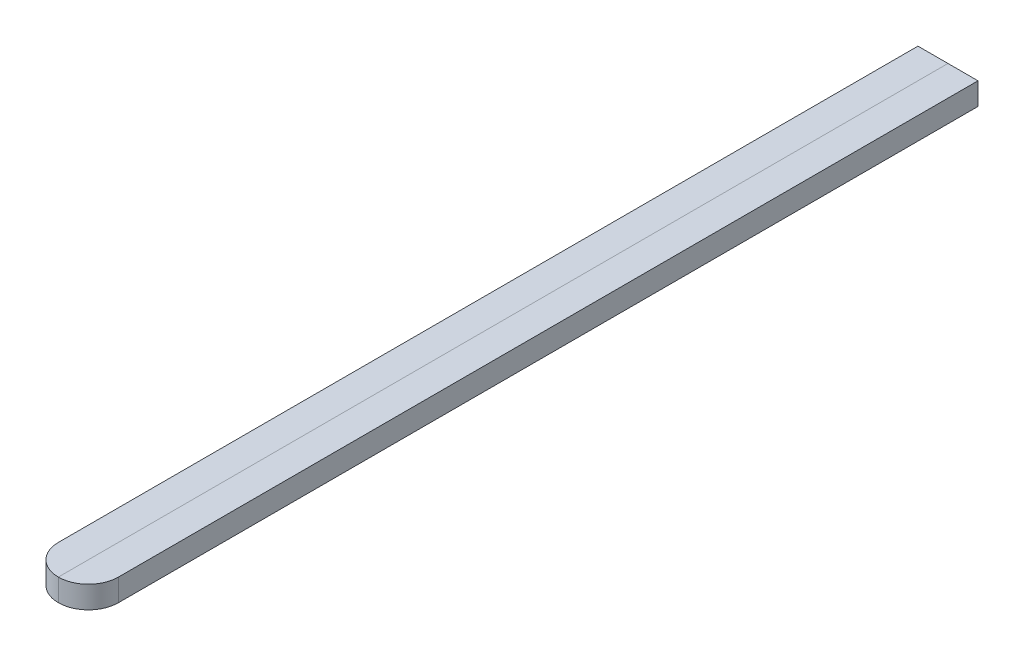
SolidWorks part; units mm, degrees
ref_plane "Front Plane" through (0, 0, 0) normal (0, 0, 1) x (1, 0, 0)
ref_plane "Top Plane" through (0, 0, 0) normal (0, 1, 0) x (1, 0, 0)
ref_plane "Right Plane" through (0, 0, 0) normal (1, 0, 0) x (0, 0, -1)
sketch "Sketch1" plane through (0, 0, 0) normal (0, 0, 1) x (1, 0, 0)
  line L1 (0, 0) -> (6.858, 0)
  line L2 (0, 0) -> (0, 2.54)
  line L3 (0, 2.54) -> (6.858, 2.54)
  line L4 (6.858, 0) -> (6.858, 2.54)
  dimension "D1" = 6.858
  dimension "D2" = 2.54
extrude "Boss-Extrude1" add sketch "Sketch1" along normal blind 101.6
ref_plane "Plane1" through (3.429, 0, 0) normal (1, 0, 0) x (0, 0, -1)
sketch "Sketch2" plane through (0, 2.54, 0) normal (0, 1, 0) x (1, 0, 0)
  line L0 (6.858, -98.171) -> (6.858, -101.6)
  line L1 (6.858, -101.6) -> (3.429, -101.6)
  line L3 (3.429, -1.397) -> (3.429, 1.397) construction
  line L4 (6.858, -101.6) -> (0, -101.6) construction
  line L5 (0, -101.6) -> (0, 0) construction
  line L6 (0, -98.171) -> (0, -101.6)
  line L7 (0, -101.6) -> (3.429, -101.6)
  arc A0 (0, -98.171) -> (6.858, -98.171) centre (3.429, -98.171) ccw
  line M2 (0, 0) -> (0, -101.6)
  line M3 (0, -101.6) -> (6.858, -101.6)
  line M4 (6.858, -101.6) -> (6.858, 0)
extrude "Cut-Extrude1" cut sketch "Sketch2" against normal up to next contours A0 M2 M3 | A0 M3 M4
split "Split1" trim tools "Plane1" bodies to split 104 resulting bodies 102 103
